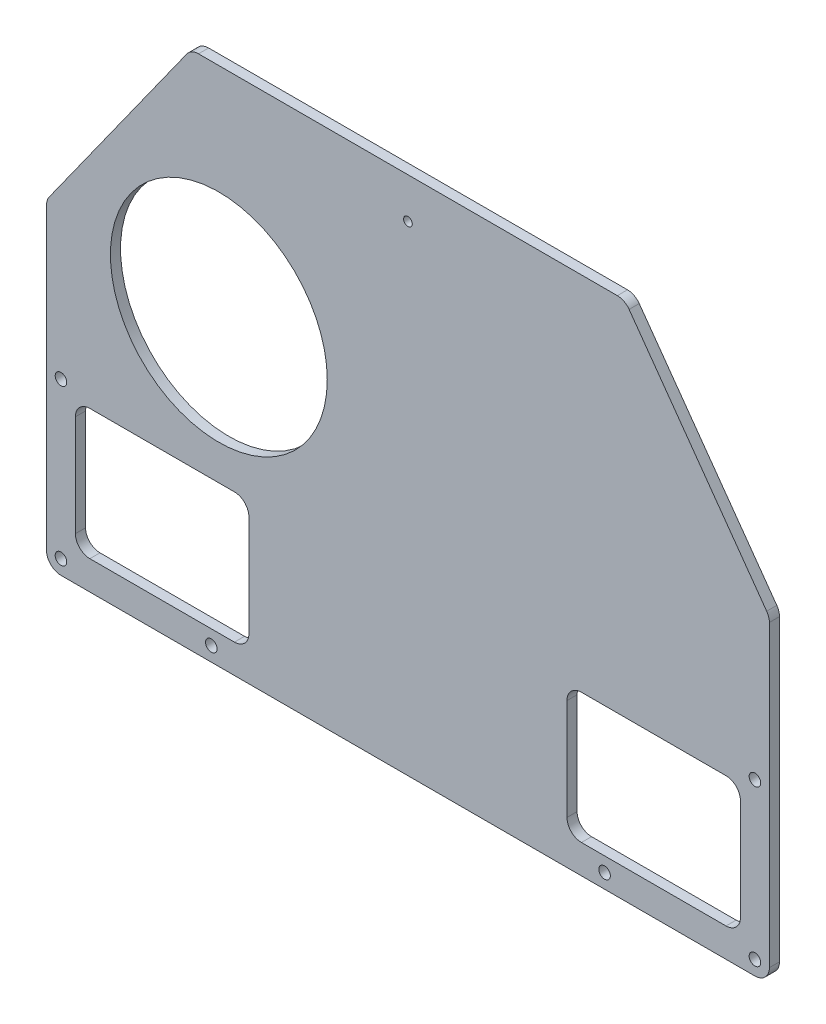
SolidWorks part; units mm, degrees
ref_plane "Plan de face" through (0, 0, 0) normal (0, 0, 1) x (1, 0, 0)
ref_plane "Plan de dessus" through (0, 0, 0) normal (0, 1, 0) x (1, 0, 0)
ref_plane "Plan de droite" through (0, 0, 0) normal (1, 0, 0) x (0, 0, -1)
sketch "Esquisse1" plane through (0, 0, 0) normal (0, 0, 1) x (1, 0, 0)
  line L1 (5, 0) -> (245, 0)
  line L2 (0, 5) -> (0, 305)
  line L3 (0, 305) -> (250, 305)
  line L4 (250, 5) -> (250, 305)
  arc A0 (250, 5) -> (245, 0) centre (245, 5) cw
  arc A1 (5, 0) -> (0, 5) centre (5, 5) cw
  point P7 (250, 0)
  point P10 (0, 0)
  dimension "D2" = 5
  dimension "D3" = 5
  dimension "D1" = 250
  dimension "D4" = 300
extrude "Boss.-Extru.1" add sketch "Esquisse1" along normal blind 3.5
sketch "Esquisse2" plane through (0, 0, 3.5) normal (0, 0, 1) x (1, 0, 0)
  line L0 (-19.0099, 5) -> (402.2953, 5) construction
  line L1 (5, 0) -> (245, 0) construction
  line L2 (5, -25.1291) -> (5, 139.966) construction
  line L3 (0, 305) -> (0, 5) construction
  line L4 (245, -22.1166) -> (245, 94.5536) construction
  line L5 (250, 5) -> (250, 305) construction
  line L6 (-9.3926, 58.8) -> (267.0784, 58.8) construction
  circle A0 centre (5, 5) radius 2
  circle A1 centre (245, 5) radius 2
  circle A2 centre (5, 58.8) radius 2
  circle A3 centre (245, 58.8) radius 2
  dimension "D1" = 4
  dimension "D2" = 4
  dimension "D7" = 4
  dimension "D8" = 4
  dimension "D3" = 5
  dimension "D4" = 5
  dimension "D5" = 5
  dimension "D6" = 53.8
extrude "Enlèv. mat.-Extru.1" cut sketch "Esquisse2" against normal through all
sketch "Esquisse3" plane through (0, 0, 3.5) normal (0, 0, 1) x (1, 0, 0)
  line L0 (-13.1091, 5) -> (277.0265, 5) construction
  line L1 (5, 0) -> (245, 0) construction
  line L2 (0, 305) -> (0, 5) construction
  circle A0 centre (57, 5) radius 2
  circle A1 centre (193, 5) radius 2
  dimension "D3" = 4
  dimension "D4" = 4
  dimension "D1" = 5
  dimension "D2" = 136
  dimension "D5" = 57
extrude "Enlèv. mat.-Extru.2" cut sketch "Esquisse3" against normal through all
sketch "Esquisse4" plane through (0, 0, 0) normal (0, 0, -1) x (-1, 0, 0)
  line L0 (-70, 15) -> (-70, 50)
  line L1 (-65, 55) -> (-15, 55)
  line L2 (-10, 50) -> (-10, 15)
  line L3 (-15, 10) -> (-65, 10)
  line L4 (-5, 0) -> (-245, 0) construction
  line L5 (0, 305) -> (0, 5) construction
  line L6 (-185, 10) -> (-235, 10)
  line L7 (-180, 15) -> (-180, 50)
  line L8 (-185, 55) -> (-235, 55)
  line L9 (-240, 15) -> (-240, 50)
  line L10 (-250, 5) -> (-250, 305) construction
  arc A0 (-70, 50) -> (-65, 55) centre (-65, 50) cw
  arc A1 (-15, 55) -> (-10, 50) centre (-15, 50) cw
  arc A2 (-70, 15) -> (-65, 10) centre (-65, 15) ccw
  arc A3 (-10, 15) -> (-15, 10) centre (-15, 15) cw
  arc A4 (-240, 50) -> (-235, 55) centre (-235, 50) cw
  arc A5 (-180, 50) -> (-185, 55) centre (-185, 50) ccw
  arc A6 (-240, 15) -> (-235, 10) centre (-235, 15) ccw
  arc A7 (-185, 10) -> (-180, 15) centre (-185, 15) ccw
  point P9 (-70, 55)
  point P12 (-10, 55)
  point P18 (-10, 10)
  point P27 (-240, 55)
  point P30 (-180, 55)
  point P35 (-180, 10)
  dimension "D4" = 5
  dimension "D10" = 5
  dimension "D1" = 10
  dimension "D2" = 60
  dimension "D3" = 45
  dimension "D5" = 10
  dimension "D6" = 10
  dimension "D7" = 45
  dimension "D8" = 60
  dimension "D9" = 10
extrude "Enlèv. mat.-Extru.3" cut sketch "Esquisse4" against normal through all
sketch "Esquisse5" plane through (0, 0, 3.5) normal (0, 0, 1) x (1, 0, 0)
  line L0 (0, 110) -> (50, 180)
  line L2 (50, 180) -> (200, 180)
  line L3 (200, 180) -> (250, 110)
  line L5 (125, 623.6506) -> (125, -13.6506) construction
  line L6 (250, 305) -> (0, 305) construction
  line L7 (5, 0) -> (245, 0) construction
  point P12 (125, 305)
  point P13 (125, 180)
  dimension "D1" = 150
  dimension "D2" = 180
  dimension "D3" = 110
  dimension "D4" = 110
extrude "Enlèv. mat.-Extru.4" cut sketch "Esquisse5" against normal through all and the other way through all
sketch "Esquisse6" plane through (0, 0, 3.5) normal (0, 0, 1) x (1, 0, 0)
  line L0 (50, 180) -> (200, 180) construction
  line L4 (125, 209.3374) -> (125, 98.3712) construction
  circle A0 centre (125, 166) radius 1.5
  dimension "D3" = 3
  dimension "D1" = 14
  dimension "D4" = 75
extrude "Enlèv. mat.-Extru.5" cut sketch "Esquisse6" against normal through all
fillet "Congé1" radius 5 4 edges at (250, 110, 1.75) (200, 180, 1.75) (50, 180, 1.75) (0, 110, 1.75)
sketch "Esquisse7" plane through (0, 0, 3.5) normal (0, 0, 1) x (1, 0, 0)
  line L0 (0, 108.3977) -> (0, 5) construction
  line L1 (0.9313, 111.3039) -> (48.5044, 177.9062) construction
  circle A0 centre (59.6, 104.6468) radius 37.5
  dimension "D3" = 75
  dimension "D1" = 59.6
  dimension "D2" = 51.61
extrude "Enlèv. mat.-Extru.6" cut sketch "Esquisse7" against normal through all
